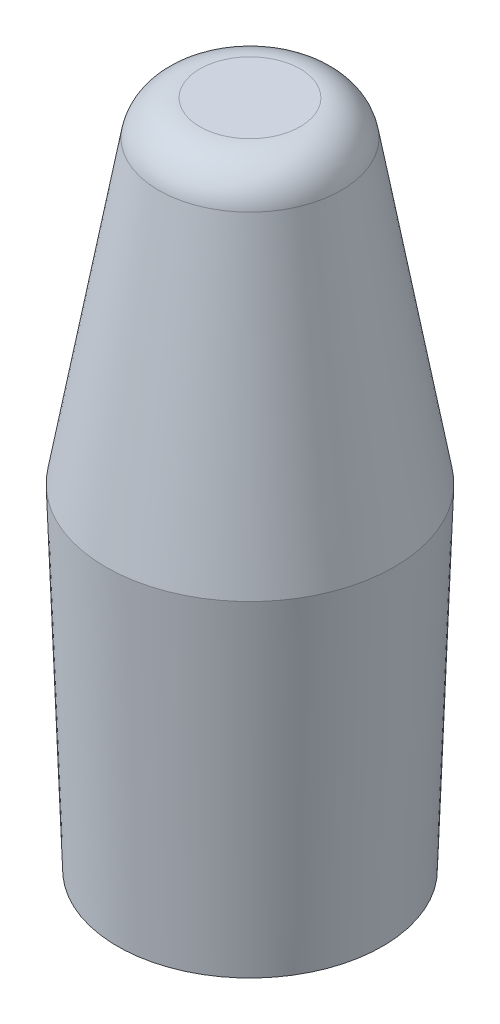
SolidWorks part; units mm, degrees
ref_plane "Front Plane" through (0, 0, 0) normal (0, 0, 1) x (1, 0, 0)
ref_plane "Top Plane" through (0, 0, 0) normal (0, 1, 0) x (1, 0, 0)
ref_plane "Right Plane" through (0, 0, 0) normal (1, 0, 0) x (0, 0, -1)
sketch "Sketch1" plane through (0, 0, 0) normal (0, 1, 0) x (1, 0, 0)
  circle A0 centre (0, 0) radius 1.725
  dimension "D1" = 3.45
extrude "Boss-Extrude1" add sketch "Sketch1" along normal blind 4 draft 10
sketch "Sketch2" plane through (0, 0, 0) normal (0, -1, 0) x (1, 0, 0)
  circle A0 centre (0, 0) radius 1.725
  dimension "D1" = 3.45
extrude "Boss-Extrude2" add sketch "Sketch2" along normal blind 4 draft 2 separate body
fillet "Fillet5" radius 0.5 1 edges at (0, 4, 1.0197)
